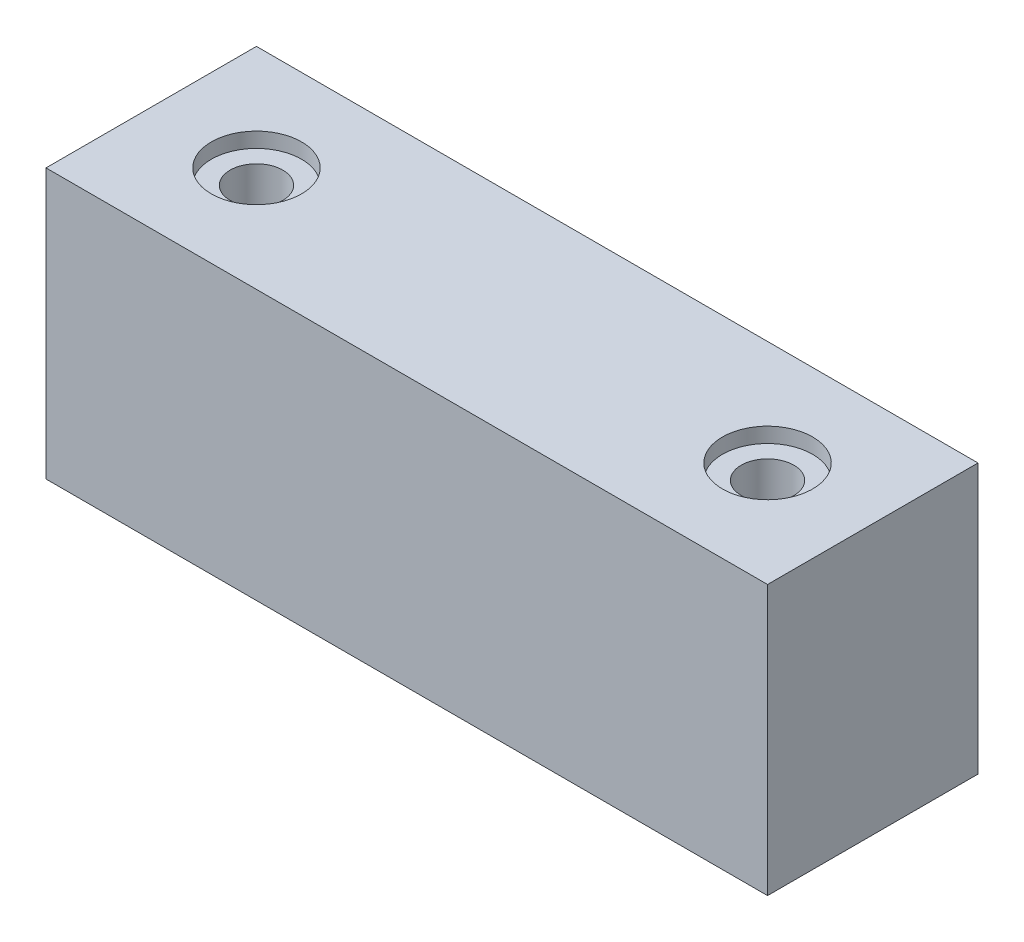
SolidWorks part; units mm, degrees
material "1060 Alloy"
ref_plane "Front Plane" through (0, 0, 0) normal (0, 0, 1) x (1, 0, 0)
ref_plane "Top Plane" through (0, 0, 0) normal (0, 1, 0) x (1, 0, 0)
ref_plane "Right Plane" through (0, 0, 0) normal (1, 0, 0) x (0, 0, -1)
sketch "Sketch1" plane through (0, 0, 0) normal (0, 0, 1) x (1, 0, 0)
  line L1 (-128.2262, -19.6505) -> (176.5738, -19.6505)
  line L2 (-128.2262, -19.6505) -> (-128.2262, -133.4814)
  line L3 (-128.2262, -133.4814) -> (176.5738, -133.4814)
  line L4 (176.5738, -19.6505) -> (176.5738, -133.4814)
  dimension "D1" = 304.8
  dimension "D2" = 113.8309
extrude "Boss-Extrude1" add sketch "Sketch1" along normal blind 88.9 contours L2 L1 L4 L3
sketch "Sketch2" plane through (0, -19.6505, 0) normal (0, 1, 0) x (1, 0, 0)
  line L0 (-128.2262, -88.9) -> (-128.2262, 0) construction
  line L1 (-128.2262, -88.9) -> (176.5738, -88.9) construction
  line L2 (24.1738, 0) -> (24.1738, -150.1325) construction
  line L4 (-128.2262, 0) -> (176.5738, 0) construction
  circle A0 centre (-83.7762, -44.45) radius 19.05
  circle A1 centre (132.1238, -44.45) radius 19.05
  dimension "D1" = 38.1
  dimension "D2" = 44.45
  dimension "D3" = 44.45
extrude "Cut-Extrude1" cut sketch "Sketch2" against normal blind 6.35
sketch "Sketch3" plane through (0, -26.0005, 0) normal (0, 1, 0) x (1, 0, 0)
  line L0 (24.1738, 0) -> (24.1738, -130.286) construction
  line L1 (-128.2262, 0) -> (176.5738, 0) construction
  circle A0 centre (-83.7762, -44.45) radius 11.1125
  circle A1 centre (132.1238, -44.45) radius 11.1125
  dimension "D1" = 22.225
extrude "Cut-Extrude2" cut sketch "Sketch3" against normal through all
equation "\"H\"= ( ( 3 * \"Load\" * ( 1 / 4.45 ) * \"span\" ) / ( \"Cw\" * \"stress\" ) ) ^ ( 1 / 3 )"
equation "\"Load\"= 2000'Load in Newtons"
equation "\"SF\"= 4"
equation "\"Cw\"= 3.5'inches"
equation "\"stress\"= 42.8'psi"
equation "\"span\"= 10'in"
equation "\"D2@Sketch1\"=\"H\""
equation "\"D1@Boss-Extrude1\"=\"Cw\""
